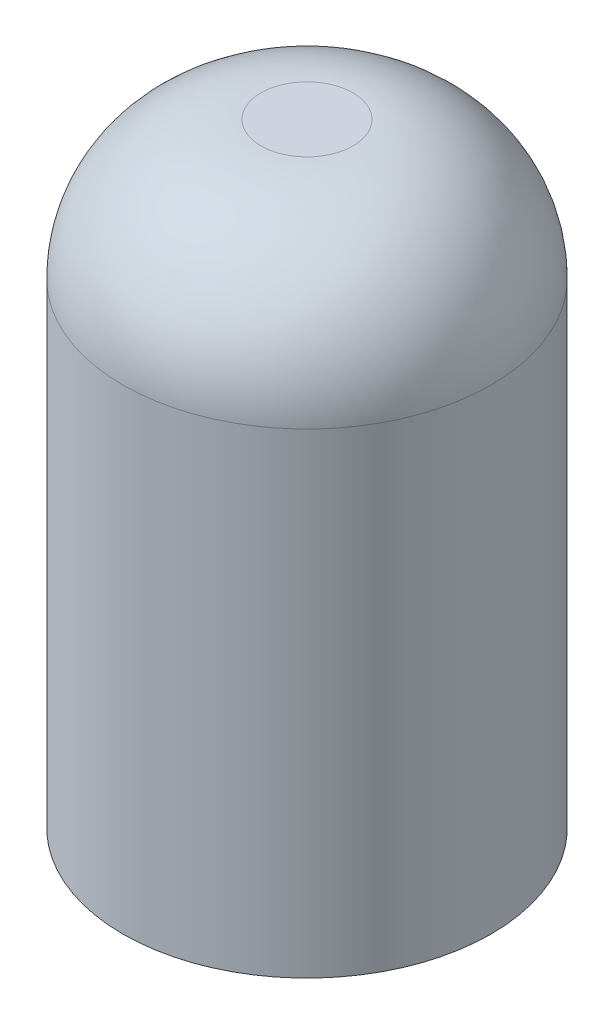
SolidWorks part; units mm, degrees
ref_plane "Front Plane" through (0, 0, 0) normal (0, 0, 1) x (1, 0, 0)
ref_plane "Top Plane" through (0, 0, 0) normal (0, 1, 0) x (1, 0, 0)
ref_plane "Right Plane" through (0, 0, 0) normal (1, 0, 0) x (0, 0, -1)
sketch "Sketch1" plane through (0, 0, 0) normal (0, 0, 1) x (1, 0, 0)
  line L0 (0, 0) -> (60, 0)
  line L1 (60, 0) -> (60, 155)
  line L2 (15, 200) -> (0, 200)
  line L3 (0, 200) -> (0, 0)
  arc A0 (60, 155) -> (15, 200) centre (15, 155) ccw
  dimension "D1" = 200
  dimension "D2" = 60
  dimension "D3" = 155
revolve "Revolve3" add sketch "Sketch1" angle 360 about L3
shell "Shell3" thickness 2
